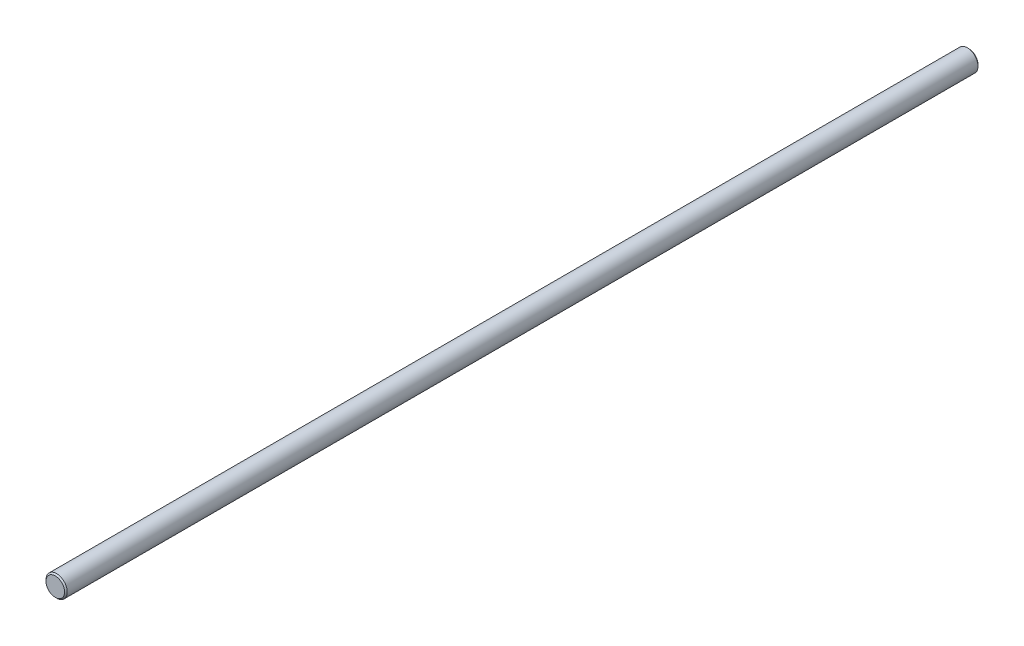
SolidWorks part; units mm, degrees
ref_plane "Alzado" through (0, 0, 0) normal (0, 0, 1) x (1, 0, 0)
ref_plane "Planta" through (0, 0, 0) normal (0, 1, 0) x (1, 0, 0)
ref_plane "Vista lateral" through (0, 0, 0) normal (1, 0, 0) x (0, 0, -1)
sketch "Croquis1" plane through (0, 0, 0) normal (0, 0, 1) x (1, 0, 0)
  circle A0 centre (0, 0) radius 4
  dimension "D1" = 8
extrude "Saliente-Extruir1" add sketch "Croquis1" against normal up to surface (343.6 mm away)
chamfer "Chaflán1" distance 0.5 angle 45 2 edges at (4, 0, 0) (0, -4, -343.6)
